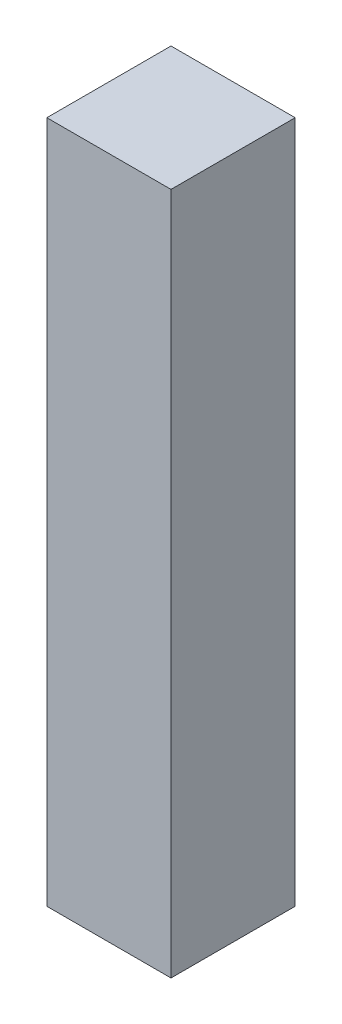
SolidWorks part; units mm, degrees
ref_plane "Front Plane" through (0, 0, 0) normal (0, 0, 1) x (1, 0, 0)
ref_plane "Top Plane" through (0, 0, 0) normal (0, 1, 0) x (1, 0, 0)
ref_plane "Right Plane" through (0, 0, 0) normal (1, 0, 0) x (0, 0, -1)
sketch "Sketch1" plane through (0, 0, 0) normal (0, 1, 0) x (1, 0, 0)
  line L1 (-50, -50) -> (50, -50)
  line L2 (-50, -50) -> (-50, 50)
  line L3 (-50, 50) -> (50, 50)
  line L4 (50, -50) -> (50, 50)
  line L5 (-50, -50) -> (50, 50) construction
  line L6 (-50, 50) -> (50, -50) construction
  point P0 (0, 0)
  dimension "D1" = 100
  dimension "D2" = 100
extrude "Boss-Extrude1" add sketch "Sketch1" along normal blind 550
